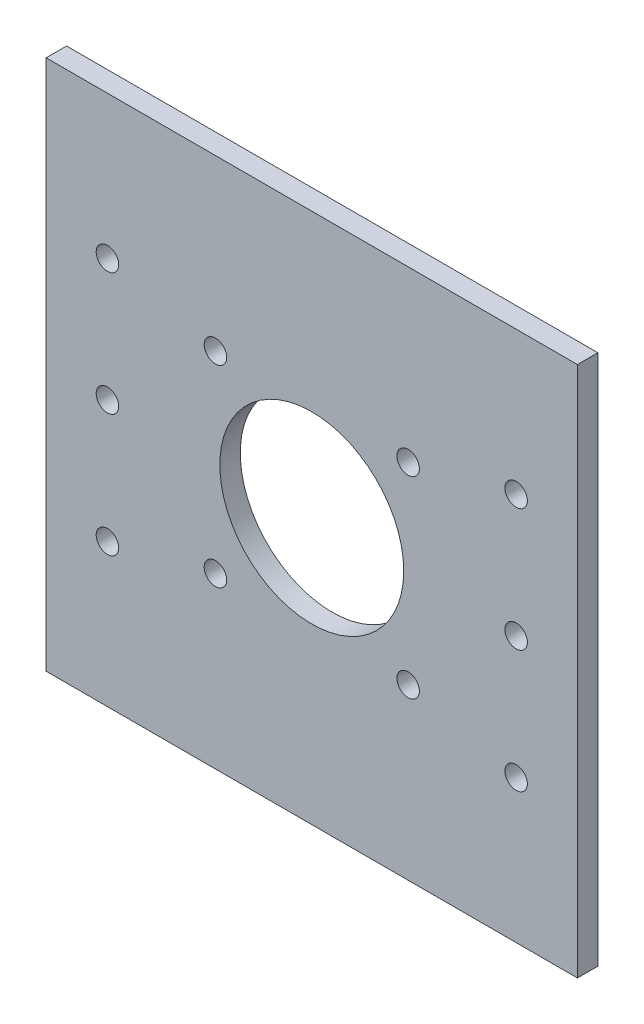
SolidWorks part; units mm, degrees
ref_plane "前视基准面" through (0, 0, 0) normal (0, 0, 1) x (1, 0, 0)
ref_plane "上视基准面" through (0, 0, 0) normal (0, 1, 0) x (1, 0, 0)
ref_plane "右视基准面" through (0, 0, 0) normal (1, 0, 0) x (0, 0, -1)
sketch "草图1" plane through (0, 0, 0) normal (0, 0, 1) x (1, 0, 0)
  line L0 (-50, 65) -> (-50, -65) construction
  line L1 (65, -65) -> (-65, -65)
  line L2 (65, -65) -> (65, 65)
  line L3 (65, 65) -> (-65, 65)
  line L4 (-65, -65) -> (-65, 65)
  line L5 (65, -65) -> (-65, 65) construction
  line L6 (65, 65) -> (-65, -65) construction
  line L7 (23.5714, -23.5714) -> (-23.5714, -23.5714) construction
  line L8 (23.5714, -23.5714) -> (23.5714, 23.5714) construction
  line L9 (23.5714, 23.5714) -> (-23.5714, 23.5714) construction
  line L10 (-23.5714, -23.5714) -> (-23.5714, 23.5714) construction
  line L11 (23.5714, -23.5714) -> (-23.5714, 23.5714) construction
  line L12 (23.5714, 23.5714) -> (-23.5714, -23.5714) construction
  line L13 (-50, -65) -> (0, -65) construction
  line L14 (0, -65) -> (0, 65) construction
  line L15 (-65, 0) -> (0, 0) construction
  circle A0 centre (0, 0) radius 22.5
  circle A1 centre (-23.5714, 23.5714) radius 2.75
  circle A2 centre (23.5714, 23.5714) radius 2.75
  circle A3 centre (23.5714, -23.5714) radius 2.75
  circle A4 centre (-23.5714, -23.5714) radius 2.75
  circle A5 centre (-50, 30) radius 2.75
  circle A6 centre (-50, 0) radius 2.75
  circle A7 centre (-50, -30) radius 2.75
  circle A8 centre (50, -30) radius 2.75
  circle A9 centre (50, 0) radius 2.75
  circle A10 centre (50, 30) radius 2.75
  point P0 (0, 0)
  dimension "D3" = 45
  dimension "D4" = 5.5
  dimension "D5" = 66.67
  dimension "D6" = 5.5
  dimension "D7" = 30
  dimension "D1" = 130
  dimension "D2" = 130
  dimension "D8" = 15
extrude "凸台-拉伸1" add sketch "草图1" along normal blind 5
